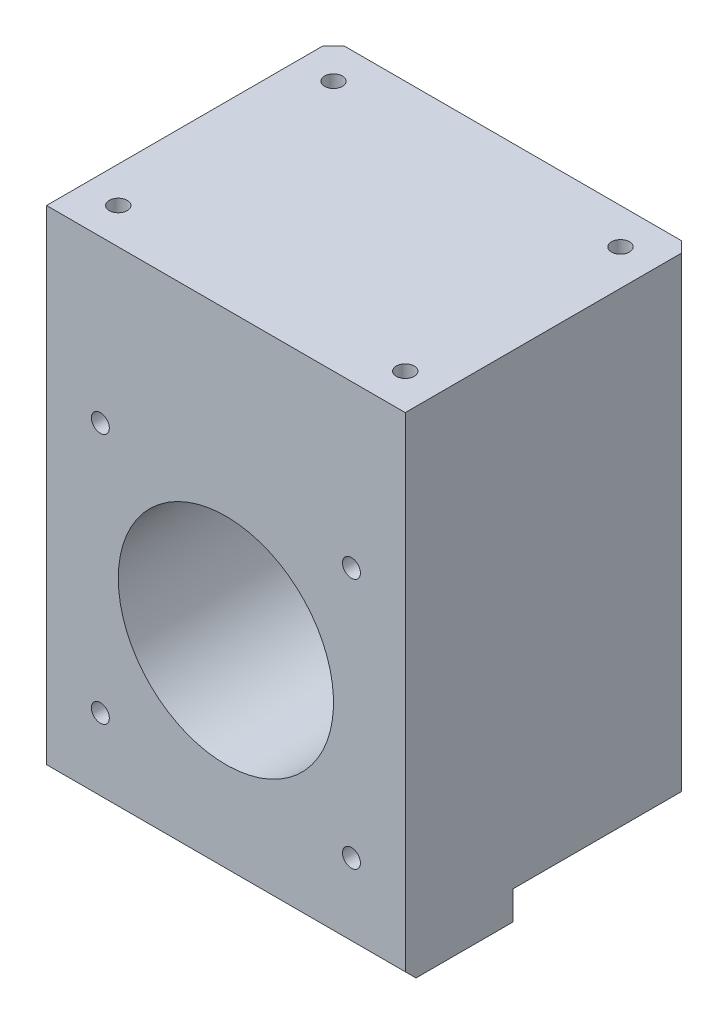
SolidWorks part; units mm, degrees
material "6061 Alloy"
ref_plane "Front Plane" through (0, 0, 0) normal (0, 0, 1) x (1, 0, 0)
ref_plane "Top Plane" through (0, 0, 0) normal (0, 1, 0) x (1, 0, 0)
ref_plane "Right Plane" through (0, 0, 0) normal (1, 0, 0) x (0, 0, -1)
sketch "Sketch1" plane through (0, 0, 0) normal (0, 1, 0) x (1, 0, 0)
  line L1 (-50, -40) -> (50, -40)
  line L2 (-50, -40) -> (-50, 40)
  line L3 (-50, 40) -> (50, 40)
  line L4 (50, -40) -> (50, 40)
  line L5 (-50, -40) -> (50, 40) construction
  line L6 (-50, 40) -> (50, -40) construction
  point P0 (0, 0)
  dimension "D1" = 100
  dimension "D2" = 80
extrude "Boss-Extrude1" add sketch "Sketch1" along normal blind 138
sketch "Sketch2" plane through (0, 0, 0) normal (0, -1, 0) x (1, 0, 0)
  line L0 (50, 40) -> (50, -40) construction
  line L1 (-50, -40) -> (50, -40)
  line L2 (-50, -40) -> (-50, 10)
  line L3 (-50, 10) -> (50, 10)
  line L4 (50, -40) -> (50, 10)
  dimension "D1" = 50
extrude "Cut-Extrude1" cut sketch "Sketch2" against normal blind 8
hole_wizard "M6 Tapped Hole1" positions "Sketch3" profile "Sketch5" tap size "M6" standard "GB"
sketch "Sketch3" plane through (0, 8, 0) normal (0, -1, 0) x (-1, 0, 0)
  line L0 (0, 44) -> (0, -44) construction
  line L1 (50, 40) -> (-50, 40) construction
  line L2 (-50, 40) -> (-50, -10) construction
  line L3 (-50, -10) -> (50, -10) construction
  point P0 (-40, 25)
  point P2 (-40, 0)
  point P7 (40, 0)
  point P8 (40, 25)
  dimension "D1" = 15
  dimension "D2" = 10
  dimension "D3" = 10
sketch "Sketch5" plane through (40, 8, -25) normal (1, 0, 0) x (0, 0, -1)
  line L0 (0, 0) -> (0, 16.5022)
  line L1 (0, 16.5022) -> (2.5, 15)
  line L2 (2.5, 15) -> (2.5, 0)
  line L5 (2.5, 0) -> (0, 0)
  line L10 (0, 16.5022) -> (-2.5, 15) construction
  line L11 (0, -6.35) -> (0, 107.95) construction
  dimension "Tap Drill Dia." = 5
  dimension "Tap Drill Depth" = 15
  dimension "Drill Angle" = 118
cosmetic thread "Hole Thread1" parameters "D1"=12, "D2"=6
cosmetic thread "Hole Thread2" parameters "D1"=12, "D2"=6
cosmetic thread "Hole Thread3" parameters "D1"=12, "D2"=6
cosmetic thread "Hole Thread4" parameters "D1"=12, "D2"=6
sketch "Sketch6" plane through (0, 0, -40) normal (0, 0, -1) x (-1, 0, 0)
  line L0 (-50, 138) -> (50, 138) construction
  circle A0 centre (0, 58) radius 30
  dimension "D2" = 60
  dimension "D1" = 80
extrude "Cut-Extrude2" cut sketch "Sketch6" against normal through all
hole_wizard "M6 Tapped Hole2" positions "Sketch7" profile "Sketch8" tap size "M6" standard "GB"
sketch "Sketch7" plane through (0, 138, 0) normal (0, 1, 0) x (1, 0, 0)
  line L0 (-55, 0) -> (55, 0) construction
  line L1 (0, -44) -> (0, 44) construction
  line L2 (-50, 40) -> (-50, -40) construction
  line L3 (50, 40) -> (-50, 40) construction
  point P0 (-40, 30)
  point P5 (-40, -30)
  point P8 (40, -30)
  point P9 (40, 30)
  dimension "D1" = 10
  dimension "D2" = 10
sketch "Sketch8" plane through (-40, 138, -30) normal (1, 0, 0) x (0, 0, 1)
  line L0 (0, 0) -> (0, 16.5022)
  line L1 (0, 16.5022) -> (2.5, 15)
  line L2 (2.5, 15) -> (2.5, 0)
  line L5 (2.5, 0) -> (0, 0)
  line L10 (0, 16.5022) -> (-2.5, 15) construction
  line L11 (0, -6.35) -> (0, 107.95) construction
  dimension "Tap Drill Dia." = 5
  dimension "Tap Drill Depth" = 15
  dimension "Drill Angle" = 118
cosmetic thread "Hole Thread5" parameters "D1"=12, "D2"=6
cosmetic thread "Hole Thread6" parameters "D1"=12, "D2"=6
cosmetic thread "Hole Thread7" parameters "D1"=12, "D2"=6
cosmetic thread "Hole Thread8" parameters "D1"=12, "D2"=6
hole_wizard "M6 Tapped Hole3" positions "Sketch9" profile "Sketch10" tap size "M6" standard "GB"
sketch "Sketch9" plane through (0, 0, -40) normal (0, 0, -1) x (-1, 0, 0)
  line L0 (0, 44) -> (0, -44) construction
  circle A0 centre (0, 58) radius 30 construction
  point P0 (-35, 23)
  point P2 (-35, 93)
  point P11 (35, 93)
  point P12 (35, 23)
  dimension "D1" = 35
  dimension "D2" = 35
  dimension "D3" = 35
sketch "Sketch10" plane through (35, 23, -40) normal (1, 0, 0) x (0, 1, 0)
  line L0 (0, 0) -> (0, 11.5022)
  line L1 (0, 11.5022) -> (2.5, 10)
  line L2 (2.5, 10) -> (2.5, 0)
  line L5 (2.5, 0) -> (0, 0)
  line L10 (0, 11.5022) -> (-2.5, 10) construction
  line L11 (0, -6.35) -> (0, 107.95) construction
  dimension "Tap Drill Dia." = 5
  dimension "Tap Drill Depth" = 10
  dimension "Drill Angle" = 118
cosmetic thread "Hole Thread9" parameters "D1"=12, "D2"=6
cosmetic thread "Hole Thread10" parameters "D1"=12, "D2"=6
cosmetic thread "Hole Thread11" parameters "D1"=12, "D2"=6
cosmetic thread "Hole Thread12" parameters "D1"=12, "D2"=6
hole_wizard "M6 Tapped Hole4" positions "Sketch12" profile "Sketch14" tap size "M6" standard "GB"
sketch "Sketch12" plane through (0, 0, 40) normal (0, 0, 1) x (1, 0, 0)
  line L0 (0, 58) -> (0, 138) construction
  line L2 (0, 58) -> (-50, 58) construction
  line L3 (-50, 138) -> (-50, 0) construction
  line L6 (-50, 138) -> (50, 138) construction
  circle A0 centre (0, 58) radius 30 construction
  point P0 (-35, 93)
  point P22 (35, 93)
  point P23 (35, 23)
  point P24 (-35, 23)
  dimension "D1" = 70
  dimension "D2" = 70
sketch "Sketch14" plane through (-35, 93, 40) normal (1, 0, 0) x (0, -1, 0)
  line L0 (0, 0) -> (0, 16.5022)
  line L1 (0, 16.5022) -> (2.5, 15)
  line L2 (2.5, 15) -> (2.5, 0)
  line L5 (2.5, 0) -> (0, 0)
  line L10 (0, 16.5022) -> (-2.5, 15) construction
  line L11 (0, -6.35) -> (0, 107.95) construction
  dimension "Tap Drill Dia." = 5
  dimension "Tap Drill Depth" = 15
  dimension "Drill Angle" = 118
cosmetic thread "Hole Thread13" parameters "D1"=12, "D2"=6
cosmetic thread "Hole Thread14" parameters "D1"=12, "D2"=6
cosmetic thread "Hole Thread15" parameters "D1"=12, "D2"=6
cosmetic thread "Hole Thread16" parameters "D1"=12, "D2"=6
chamfer "Chamfer1" distance 3 angle 45 3 edges at (-50, 73, -40) (50, 73, -40) (0, 0, 40)
